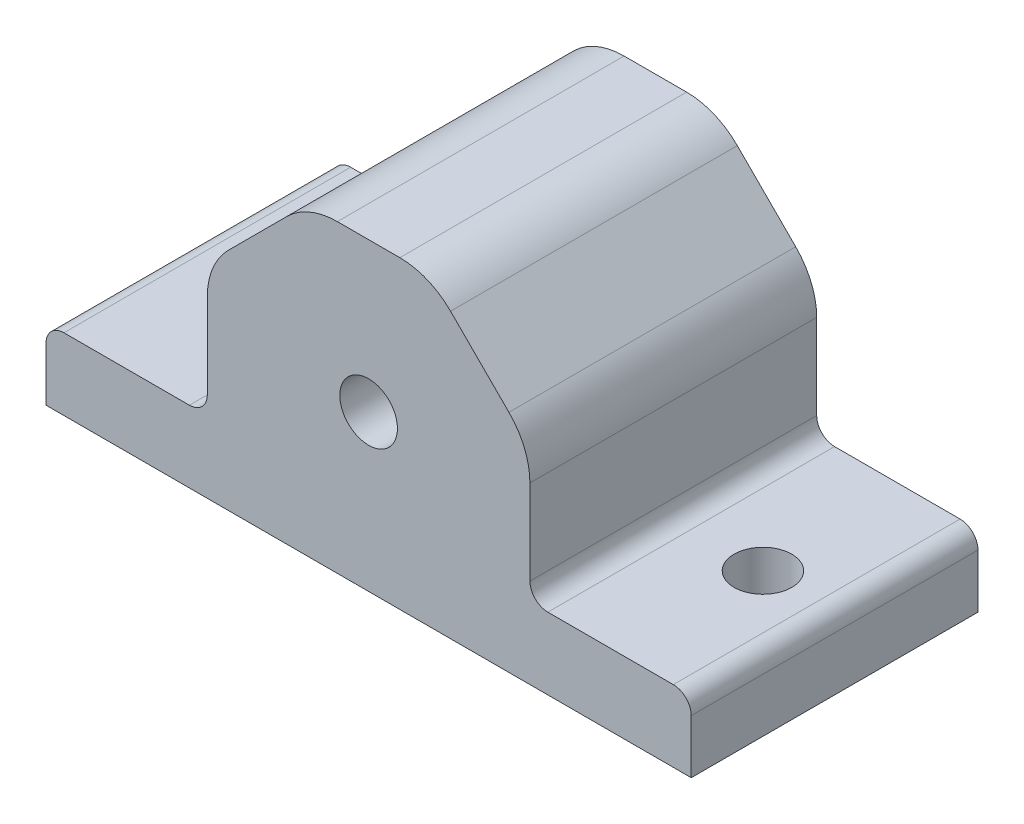
SolidWorks part; units mm, degrees
material "1060 Alloy"
ref_plane "Front Plane" through (0, 0, 0) normal (0, 0, 1) x (1, 0, 0)
ref_plane "Top Plane" through (0, 0, 0) normal (0, 1, 0) x (1, 0, 0)
ref_plane "Right Plane" through (0, 0, 0) normal (1, 0, 0) x (0, 0, -1)
ref_plane "Plane1" through (0, 0, 25.4) normal (0, 0, 1) x (1, 0, 0)
sketch "Sketch1" plane through (0, 0, 0) normal (0, 0, 1) x (1, 0, 0)
  line L0 (-5.3975, 26.9875) -> (5.3975, 26.9875)
  line L3 (-5.3975, 26.9875) -> (-14.2875, 18.0975)
  line L4 (-14.2875, 18.0975) -> (-14.2875, 6.35)
  line L5 (-14.2875, 6.35) -> (-28.575, 6.35)
  line L6 (-28.575, 6.35) -> (-28.575, 0)
  line L7 (-28.575, 0) -> (28.575, 0)
  line L8 (28.575, 0) -> (28.575, 6.35)
  line L9 (28.575, 6.35) -> (14.2875, 6.35)
  line L10 (14.2875, 6.35) -> (14.2875, 18.0975)
  line L11 (14.2875, 18.0975) -> (5.3975, 26.9875)
  line L13 (0, 0) -> (0, 26.9875) construction
  point P0 (0, 0)
  dimension "D1" = 57.15
  dimension "D2" = 6.35
  dimension "D3" = 10.795
  dimension "D4" = 26.9875
  dimension "D7" = 11.7475
  dimension "D8" = 28.575
extrude "Boss-Extrude1" add sketch "Sketch1" against normal blind 25.4
fillet "Fillet1" radius 1.5875 4 edges at (-14.2875, 6.35, -12.7) (-28.575, 6.35, -12.7) (14.2875, 6.35, -12.7) (28.575, 6.35, -12.7)
fillet "Fillet3" radius 6.35 4 edges at (14.2875, 18.0975, -12.7) (-14.2875, 18.0975, -12.7) (-5.3975, 26.9875, -12.7) (5.3975, 26.9875, -12.7)
sketch "Sketch2" plane through (0, 0, 0) normal (0, -1, 0) x (1, 0, 0)
  line L0 (-28.575, -25.4) -> (-28.575, 0) construction
  line L1 (0, -25.4) -> (0, 0) construction
  line L2 (-28.575, -25.4) -> (28.575, -25.4) construction
  line L3 (-28.575, 0) -> (28.575, 0) construction
  circle A0 centre (-22.225, -12.7) radius 2.5527
  point P4 (-28.575, -12.7)
  dimension "D1" = 5.1054
  dimension "D2" = 44.45
extrude "Cut-Extrude1" cut sketch "Sketch2" against normal through all
mirror "Mirror1" about plane through (0, 0, 0) normal (1, 0, 0) of "Cut-Extrude1"
sketch "Sketch4" plane through (0, 0, -25.4) normal (0, 0, -1) x (-1, 0, 0)
  circle A0 centre (0, 13.7668) radius 2.5527
  point P3 (0, 0)
  dimension "D2" = 5.1054
  dimension "D1" = 13.7668
extrude "Cut-Extrude2" cut sketch "Sketch4" against normal through all
